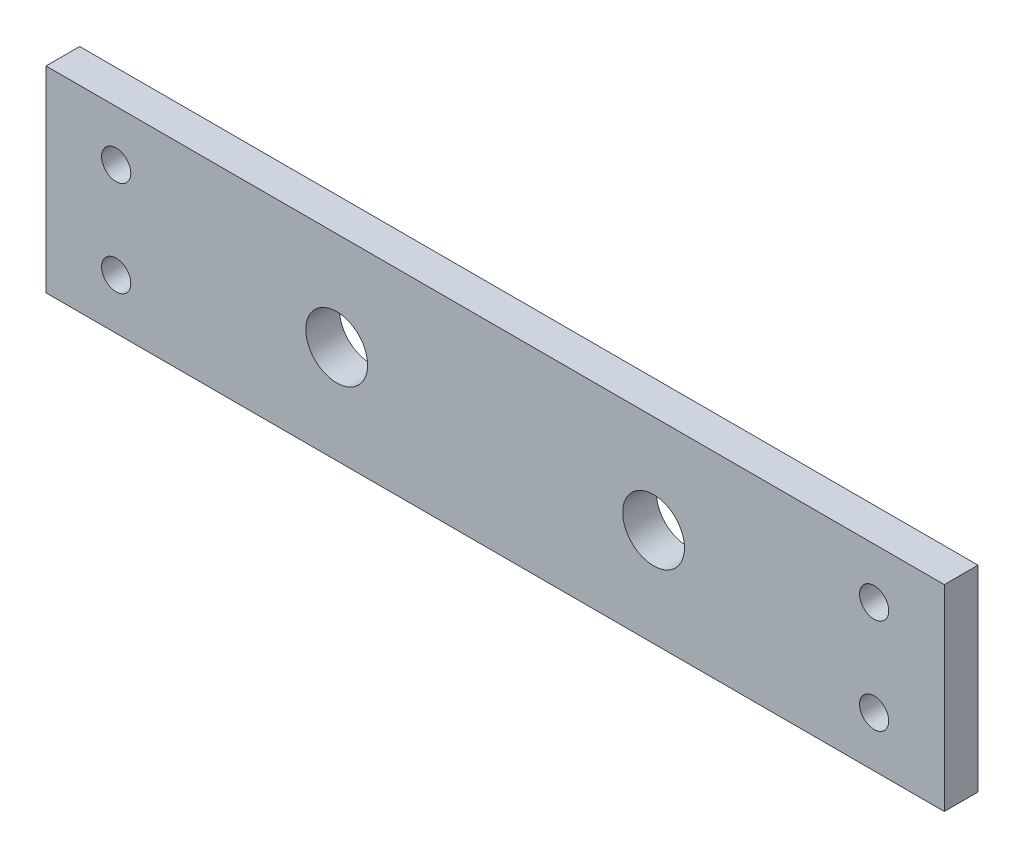
SolidWorks part; units mm, degrees
ref_plane "前视基准面" through (0, 0, 0) normal (0, 0, 1) x (1, 0, 0)
ref_plane "上视基准面" through (0, 0, 0) normal (0, 1, 0) x (1, 0, 0)
ref_plane "右视基准面" through (0, 0, 0) normal (1, 0, 0) x (0, 0, -1)
sketch "Sketch1" plane through (0, 0, 0) normal (0, 0, 1) x (1, 0, 0)
  line L1 (-80, 17.5) -> (80, 17.5)
  line L2 (-80, 17.5) -> (-80, -17.5)
  line L3 (-80, -17.5) -> (80, -17.5)
  line L4 (80, 17.5) -> (80, -17.5)
  line L5 (0, -17.5) -> (0, 17.5) construction
  line L6 (-80, 0) -> (80, 0) construction
  point P0 (0, 0)
  dimension "D1" = 160
  dimension "D2" = 35
extrude "Boss-Extrude1" add sketch "Sketch1" along normal blind 6
sketch "Sketch2" plane through (0, 0, 6) normal (0, 0, 1) x (1, 0, 0)
  line L0 (80, 17.5) -> (-80, 17.5) construction
  line L1 (-80, -17.5) -> (80, -17.5) construction
  circle A0 centre (67.5, 8.5) radius 2.6
  circle A1 centre (67.5, -8.5) radius 2.6
  circle A2 centre (-67.5, 8.5) radius 2.6
  circle A3 centre (-67.5, -8.5) radius 2.6
  point P13 (0, 0)
  point P14 (0, 0)
  point P15 (0, 0)
  point P16 (0, 0)
  point P17 (0, 0)
  point P18 (0, 0)
  dimension "D2" = 5.2
  dimension "D1" = 67.5
  dimension "D3" = 9
  dimension "D4" = 9
  dimension "D5" = 67.5
extrude "Cut-Extrude1" cut sketch "Sketch2" against normal up to next
sketch "Sketch3" plane through (0, 0, 6) normal (0, 0, 1) x (1, 0, 0)
  line L0 (0, -3.3) -> (0, 3.3) construction
  circle A0 centre (28.22, 0) radius 5.5
  circle A1 centre (67.5, 8.5) radius 2.6 construction
  circle A2 centre (-28.22, 0) radius 5.5
  dimension "D2" = 11
  dimension "D1" = 39.28
extrude "Cut-Extrude2" cut sketch "Sketch3" against normal up to next
